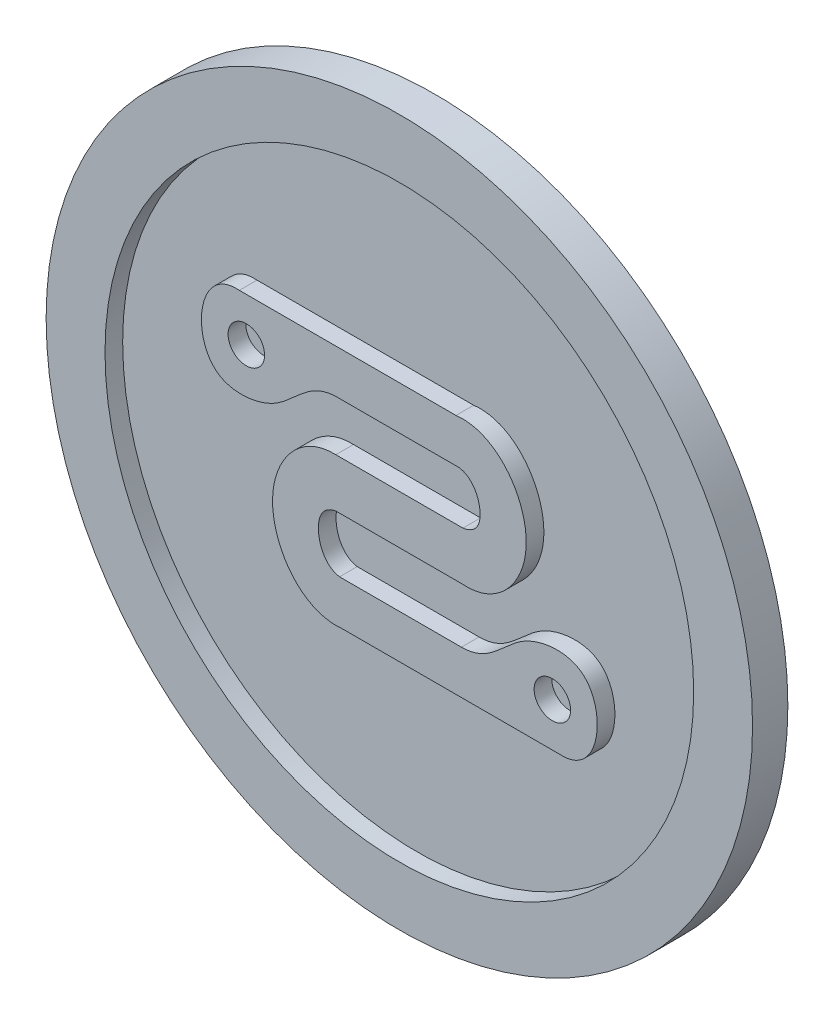
SolidWorks part; units mm, degrees
ref_plane "Płaszczyzna przednia" through (0, 0, 0) normal (0, 0, 1) x (1, 0, 0)
ref_plane "Płaszczyzna górna" through (0, 0, 0) normal (0, 1, 0) x (1, 0, 0)
ref_plane "Płaszczyzna prawa" through (0, 0, 0) normal (1, 0, 0) x (0, 0, -1)
sketch "Szkic2" plane through (0, 0, 0) normal (0, 0, 1) x (1, 0, 0)
  circle A0 centre (0, 0) radius 15
  dimension "D1" = 30
extrude "Dodanie-wyciągnięcie1" add sketch "Szkic2" along normal blind 1.5
sketch "Szkic3" plane through (0, 0, 1.5) normal (0, 0, 1) x (1, 0, 0)
  circle A0 centre (0, 0) radius 30
  dimension "D1" = 60
extrude "Dodanie-wyciągnięcie2" add sketch "Szkic3" along normal blind 1.5
sketch "Szkic4" plane through (0, 0, 3) normal (0, 0, 1) x (1, 0, 0)
  line L0 (-71.9197, 34.4135) -> (-27.9197, 34.4135) construction
  line L1 (4.8125, 10.2601) -> (-13.5902, 10.2601)
  line L2 (-5.2721, 6.5559) -> (5.0777, 6.5559)
  line L3 (-20, 0) -> (20, 0) construction
  line L4 (0, 25) -> (0, -25) construction
  line L5 (-5.3936, 2.2667) -> (5.4008, 2.2667)
  line L6 (-5.3936, -1.8732) -> (5.4008, -1.8732)
  line L7 (-4.8125, -10.2601) -> (13.5902, -10.2601)
  line L8 (5.2721, -6.5559) -> (-5.0777, -6.5559)
  circle A0 centre (-12.9962, 6.5559) radius 1.5499
  circle A2 centre (12.9962, -6.5559) radius 1.5499
  spline S0 degree 3 poles (4.8125, 10.2601) (8.4087, 10.688) (13.1963, 3.7381) (8.333, -2.0904) (5.4008, -1.8732) knots 0 0 0 0 0.552477 1 1 1 1
  spline S1 degree 3 poles (5.4008, 2.2667) (6.6932, 2.46) (7.2563, 4.4782) (6.1, 6.3998) (5.0777, 6.5559) knots 0 0 0 0 0.494793 1 1 1 1
  spline S2 degree 3 poles (-13.5902, 10.2601) (-17.1187, 10.5259) (-18.0369, 2.0467) (-9.4626, 2.8271) (-7.8373, 6.5489) (-5.2721, 6.5559) knots 0 0 0 0 0.432021 0.673133 1 1 1 1
  spline S6 degree 3 poles (-4.8125, -10.2601) (-8.4366, -10.6734) (-13.1318, -3.7053) (-8.3936, 2.373) (-5.3936, 2.2667) knots 0 0 0 0 0.544343 1 1 1 1
  spline S7 degree 3 poles (-5.3936, -1.8732) (-6.7071, -2.1116) (-7.2853, -4.3886) (-6.1086, -6.3929) (-5.0777, -6.5559) knots 0 0 0 0 0.52646 1 1 1 1
  spline S8 degree 3 poles (13.5902, -10.2601) (17.1187, -10.5259) (18.0369, -2.0467) (9.4626, -2.8271) (7.8373, -6.5489) (5.2721, -6.5559) knots 0 0 0 0 0.432021 0.673133 1 1 1 1
  point P22 (0, 0)
extrude "Dodanie-wyciągnięcie3" add sketch "Szkic4" along normal blind 1.5
sketch "Szkic5" plane through (0, 0, 3) normal (0, 0, 1) x (1, 0, 0)
  circle A0 centre (0, 0) radius 30
  circle A1 centre (0, 0) radius 25
  circle A2 centre (0, 0) radius 30 construction
  dimension "D1" = 5
extrude "Dodanie-wyciągnięcie4" add sketch "Szkic5" along normal blind 1.5
